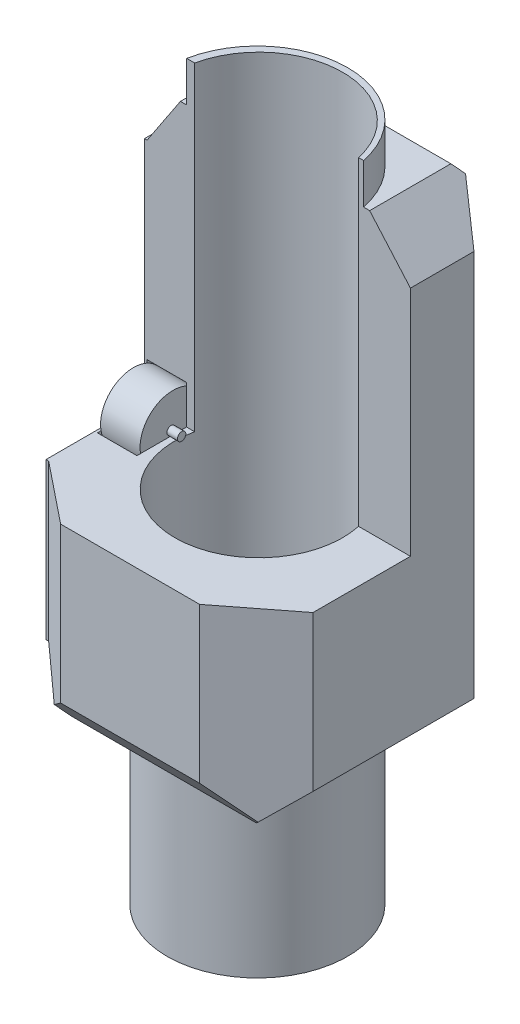
SolidWorks part; units mm, degrees
ref_plane "Front Plane" through (0, 0, 0) normal (0, 0, 1) x (1, 0, 0)
ref_plane "Top Plane" through (0, 0, 0) normal (0, 1, 0) x (1, 0, 0)
ref_plane "Right Plane" through (0, 0, 0) normal (1, 0, 0) x (0, 0, -1)
sketch "Sketch1" plane through (0, 0, 0) normal (0, 1, 0) x (1, 0, 0)
  line L1 (0, 0) -> (-100, 0)
  line L2 (0, 0) -> (0, 100)
  line L3 (0, 100) -> (-100, 100)
  line L4 (-100, 0) -> (-100, 100)
  dimension "D1" = 100
  dimension "D2" = 100
extrude "Boss-Extrude1" add sketch "Sketch1" along normal blind 180
sketch "Sketch2" plane through (0, 180, 0) normal (0, 1, 0) x (1, 0, 0)
  circle A0 centre (-51.3773, 49.0765) radius 34.2578
  point P2 (-49.1037, 52.2166)
  point P3 (-48.8771, 51.8469)
  point P4 (-51.3773, 49.0765)
extrude "Boss-Extrude2" add sketch "Sketch2" along normal mid plane 700
sketch "Sketch3" plane through (0, 0, 0) normal (1, 0, 0) x (0, 0, -1)
  line L1 (-18.5833, 361.0481) -> (133.4231, 361.0481)
  line L2 (-18.5833, 361.0481) -> (-18.5833, 643.5005)
  line L3 (-18.5833, 643.5005) -> (133.4231, 643.5005)
  line L4 (133.4231, 361.0481) -> (133.4231, 643.5005)
extrude "Cut-Extrude2" cut sketch "Sketch3" against normal blind 400
sketch "Sketch4" plane through (0, 0, 0) normal (1, 0, 0) x (0, 0, -1)
  line L0 (12.982, 0) -> (-8.9942, 25.8281)
  line L1 (-8.9942, 25.8281) -> (-18.5645, -15.2595)
  line L2 (-18.5645, -15.2595) -> (12.982, 0)
  line L3 (85.0725, -1.4481) -> (109.2376, 19.1131)
  line L4 (109.2376, 19.1131) -> (115.92, -3.2674)
  line L5 (115.92, -3.2674) -> (85.0725, -1.4481)
  line L6 (12.982, 180) -> (-8.9942, 148.5376)
  line L7 (-8.9942, 148.5376) -> (-15.4182, 193.2193)
  line L8 (-15.4182, 193.2193) -> (12.982, 180)
  line L9 (85.0725, 181.8543) -> (103.8412, 159.7959)
  line L10 (103.8412, 159.7959) -> (106.1325, 198.6474)
  line L11 (106.1325, 198.6474) -> (85.0725, 181.8543)
extrude "Cut-Extrude3" cut sketch "Sketch4" against normal blind 400
sketch "Sketch5" plane through (0, 0, 0) normal (0, 0, 1) x (1, 0, 0)
  line L0 (-85.6233, 0) -> (-106.3704, 21.4264)
  line L1 (-106.3704, 21.4264) -> (-122.2889, 3.2093)
  line L2 (-122.2889, 3.2093) -> (-93.5263, -19.8847)
  line L3 (-93.5263, -19.8847) -> (-85.6233, 0)
  line L4 (-15.695, 0) -> (0, 15.2574)
  line L5 (0, 15.2574) -> (12.1227, 15.2574)
  line L6 (12.1227, 15.2574) -> (10.5631, -19.8847)
  line L7 (10.5631, -19.8847) -> (-15.695, 0)
  line L8 (-87.1665, 180.2481) -> (-106.3704, 151.2911)
  line L9 (-106.3704, 151.2911) -> (-117.7055, 200.5011)
  line L10 (-117.7055, 200.5011) -> (-87.1665, 180.2481)
  line L11 (-15.695, 180.2481) -> (7.8338, 153.2796)
  line L12 (7.8338, 153.2796) -> (0, 193.9412)
  line L13 (0, 193.9412) -> (-15.695, 180.2481)
extrude "Cut-Extrude4" cut sketch "Sketch5" against normal blind 400
sketch "Sketch6" plane through (0, 180, 0) normal (0, 1, 0) x (1, 0, 0)
  line L1 (-112.387, 28.4004) -> (-64.2613, -10.2128)
  line L2 (-112.387, 28.4004) -> (-124.6497, -15.5119)
  line L3 (-124.6497, -15.5119) -> (-84.4064, -15.5119)
  line L4 (-64.2613, -10.2128) -> (-84.4064, -15.5119)
  line L5 (-97.0655, 135.8618) -> (-119.3755, 77.7927)
  line L6 (-97.0655, 135.8618) -> (-66.4287, 110.5752)
  line L7 (-66.4287, 110.5752) -> (-118.0433, 64.3476)
  line L8 (-119.3755, 77.7927) -> (-118.0433, 64.3476)
  line L9 (-24.6964, -21.8158) -> (11.0921, -8.9736)
  line L10 (-24.6964, -21.8158) -> (-38.5316, -11.1392)
  line L11 (-38.5316, -11.1392) -> (17.4283, 32.3938)
  line L12 (11.0921, -8.9736) -> (17.4283, 32.3938)
  line L13 (-17.4455, 140.8044) -> (35.4175, 107.2625)
  line L14 (-17.4455, 140.8044) -> (-31.7244, 103.6253)
  line L15 (-31.7244, 103.6253) -> (9.3055, 72.9964)
  line L16 (35.4175, 107.2625) -> (9.3055, 72.9964)
  point P4 (-17.4455, 140.8044)
  point P5 (-30.2763, 114.984)
  point P6 (35.4175, 107.2625)
  point P19 (-30.6265, 106.484)
  point P20 (-11.2095, 88.3109)
extrude "Cut-Extrude5" cut sketch "Sketch6" against normal blind 400
sketch "Sketch7" plane through (0, 0, 0) normal (0, 0, 1) x (1, 0, 0)
  line L1 (-146.2029, -210.0437) -> (13.9564, -210.0437)
  line L2 (-146.2029, -210.0437) -> (-146.2029, -62.6814)
  line L3 (-146.2029, -62.6814) -> (13.9564, -62.6814)
  line L4 (13.9564, -210.0437) -> (13.9564, -62.6814)
extrude "Cut-Extrude6" cut sketch "Sketch7" against normal blind 400
sketch "Sketch8" plane through (0, 0, 0) normal (0, 0, 1) x (1, 0, 0)
  line L1 (-127.1965, 251.4288) -> (20.1142, 251.4288)
  line L2 (-127.1965, 251.4288) -> (-127.1965, 413.4677)
  line L3 (-127.1965, 413.4677) -> (20.1142, 413.4677)
  line L4 (20.1142, 251.4288) -> (20.1142, 413.4677)
extrude "Cut-Extrude7" cut sketch "Sketch8" against normal blind 400
sketch "Sketch9" plane through (0, 251.4288, 0) normal (0, 1, 0) x (1, 0, 0)
  circle A0 centre (-50.809, 49.032) radius 31.8473
  point P2 (-50.6049, 49.6989)
  point P3 (-51.6378, 48.9774)
  point P4 (-50.809, 49.032)
extrude "Cut-Extrude8" cut sketch "Sketch9" against normal blind 400
sketch "Sketch10" plane through (-100, 0, 0) normal (-1, 0, 0) x (0, 0, 1)
  line L1 (-55.8114, 74.0839) -> (84.4096, 74.0839)
  line L2 (-55.8114, 74.0839) -> (-55.8114, 286.1174)
  line L3 (-55.8114, 286.1174) -> (84.4096, 286.1174)
  line L4 (84.4096, 74.0839) -> (84.4096, 286.1174)
extrude "Cut-Extrude9" cut sketch "Sketch10" against normal blind 400
sketch "Sketch11" plane through (-100, 0, 0) normal (-1, 0, 0) x (0, 0, 1)
  circle A0 centre (-50.4133, 76.2646) radius 13.6031
  point P2 (-50.4133, 76.2646)
extrude "Cut-Extrude11" cut sketch "Sketch11" against normal blind 15
sketch "Sketch12" plane through (-85, 0, 0) normal (-1, 0, 0) x (0, 0, 1)
  circle A0 centre (-50.6588, 76.2225) radius 12.4954
  point P2 (-51.6147, 75.8831)
  point P3 (-50.6588, 76.2225)
extrude "Boss-Extrude3" add sketch "Sketch12" along normal blind 15
sketch "Sketch13" plane through (-85, 0, 0) normal (1, 0, 0) x (0, 0, -1)
  circle A0 centre (49.9452, 75.9448) radius 1.5949
extrude "Boss-Extrude4" add sketch "Sketch13" along normal blind 4
sketch "Sketch14" plane through (-100, 0, 0) normal (-1, 0, 0) x (0, 0, 1)
  line L1 (-115.7243, 195.3259) -> (-14.9757, 195.3259)
  line L2 (-115.7243, 195.3259) -> (-115.7243, 305.8809)
  line L3 (-115.7243, 305.8809) -> (-14.9757, 305.8809)
  line L4 (-14.9757, 195.3259) -> (-14.9757, 305.8809)
extrude "Cut-Extrude13" cut sketch "Sketch14" against normal blind 400
sketch "Sketch15" plane through (-100, 0, 0) normal (-1, 0, 0) x (0, 0, 1)
  line L0 (-18.4618, 14.8474) -> (-80.5077, 14.8474)
  line L1 (-80.5077, 14.8474) -> (-80.5077, 160.8968)
  line L2 (-80.5077, 160.8968) -> (-55.8114, 160.8968)
  line L3 (-55.8114, 160.8968) -> (-55.8114, 74.0839)
  line L4 (-55.8114, 74.0839) -> (-18.4618, 74.0839)
  line L5 (-18.4618, 74.0839) -> (-18.4618, 14.8474)
extrude "Boss-Extrude5" add sketch "Sketch15" along normal blind 1
sketch "Sketch16" plane through (-101, 0, 0) normal (-1, 0, 0) x (0, 0, 1)
  line L1 (-69.1316, 29.9073) -> (-27.023, 29.9073)
  line L2 (-69.1316, 29.9073) -> (-69.1316, 60.3656)
  line L3 (-69.1316, 60.3656) -> (-27.023, 60.3656)
  line L4 (-27.023, 29.9073) -> (-27.023, 60.3656)
extrude "Boss-Extrude6" add sketch "Sketch16" along normal blind 5
